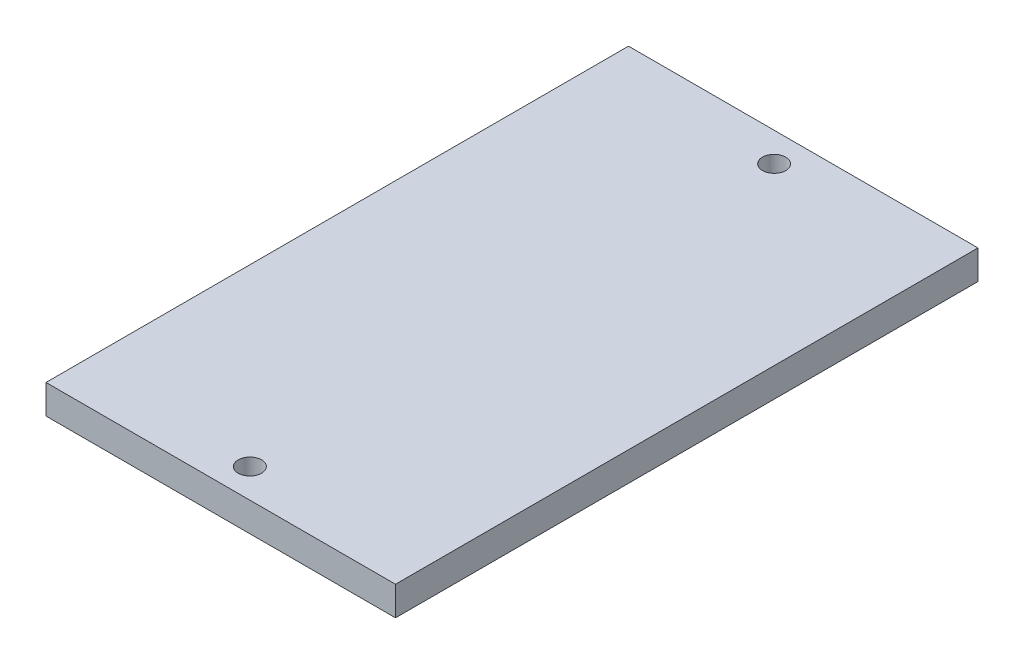
SolidWorks part; units mm, degrees
material "6061 Alloy"
ref_plane "Front" through (0, 0, 0) normal (0, 0, 1) x (1, 0, 0)
ref_plane "Top" through (0, 0, 0) normal (0, 1, 0) x (1, 0, 0)
ref_plane "Right" through (0, 0, 0) normal (1, 0, 0) x (0, 0, -1)
sketch "Sketch2" plane through (0, 0, 0) normal (0, 1, 0) x (1, 0, 0)
  line L0 (-55, 0) -> (55, 0) construction
  line L1 (-39.9715, -63.5) -> (36.2285, -63.5)
  line L2 (-39.9715, -63.5) -> (-39.9715, 63.5)
  line L3 (-39.9715, 63.5) -> (36.2285, 63.5)
  line L4 (36.2285, -63.5) -> (36.2285, 63.5)
  line L5 (-39.9715, -63.5) -> (36.2285, 63.5) construction
  line L6 (-39.9715, 63.5) -> (36.2285, -63.5) construction
  point P0 (-1.8715, 0)
  dimension "D1" = 76.2
  dimension "D2" = 127
extrude "Boss-Extrude1" add sketch "Sketch2" along normal blind 6.35
sketch "Sketch6" plane through (0, 6.35, 0) normal (0, 1, 0) x (1, 0, 0)
  circle A0 centre (-1.8715, 57.15) radius 2.54
  circle A1 centre (-1.8715, -57.15) radius 2.54
  point P4 (-39.9715, 63.5)
extrude "Cut-Extrude3" cut sketch "Sketch6" against normal blind 9.525
